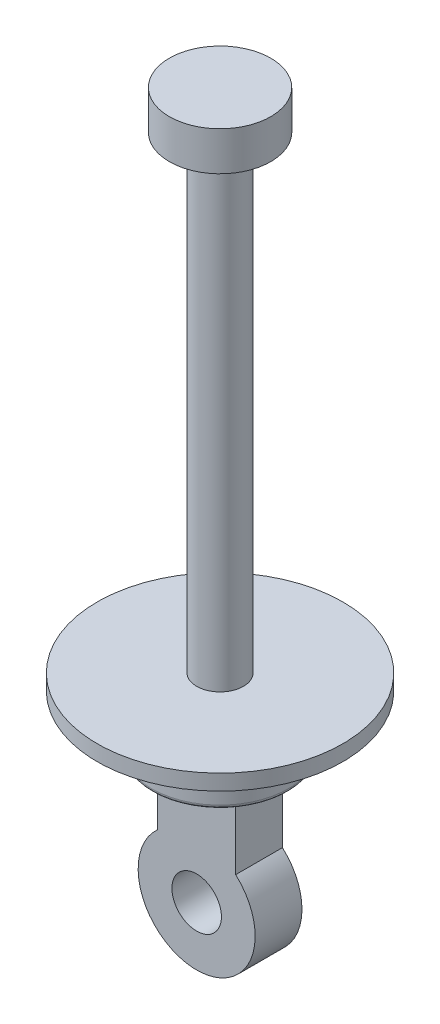
SolidWorks part; units mm, degrees
ref_plane "Front Plane" through (0, 0, 0) normal (0, 0, 1) x (1, 0, 0)
ref_plane "Top Plane" through (0, 0, 0) normal (0, 1, 0) x (1, 0, 0)
ref_plane "Right Plane" through (0, 0, 0) normal (1, 0, 0) x (0, 0, -1)
sketch "Sketch1" plane through (0, 0, 0) normal (0, 0, 1) x (1, 0, 0)
  line L1 (-15, 15) -> (15, 15)
  line L2 (-15, 15) -> (-15, -15)
  line L4 (15, 15) -> (15, -15)
  arc A0 (-15, -15) -> (15, -15) centre (0, -15) ccw
  dimension "D1" = 30
  dimension "D2" = 15
  dimension "D3" = 30
  dimension "D4" = 30
  dimension "D5" = 15
extrude "Boss-Extrude1" add sketch "Sketch1" along normal mid plane 12
sketch "Sketch2" plane through (0, 0, 6) normal (0, 0, 1) x (1, 0, 0)
  circle A0 centre (0, -15) radius 6.35
  dimension "D1" = 12.7
extrude "Cut-Extrude1" cut sketch "Sketch2" against normal through all
sketch "Sketch3" plane through (0, 0, 6) normal (0, 0, 1) x (1, 0, 0)
  line L0 (-10, -3.8197) -> (-10, 15)
  line L1 (15, 15) -> (-15, 15) construction
  line L2 (-15, 15) -> (-10, 15)
  line L4 (-15, 15) -> (-15, -15) construction
  line L5 (-15, -15) -> (15, -15) construction
  line L6 (-15, 15) -> (-15, -15)
  line L7 (0, 18.2249) -> (0, -18.3661) construction
  line L8 (15, 15) -> (15, -15)
  line L9 (15, 15) -> (10, 15)
  line L10 (10, -3.8197) -> (10, 15)
  arc A0 (-10, -3.8197) -> (-15, -15) centre (0, -15) ccw
  arc A3 (10, -3.8197) -> (15, -15) centre (0, -15) cw
  point P12 (-10, 15)
  point P25 (10, 15)
  dimension "D2" = 5
extrude "Cut-Extrude2" cut sketch "Sketch3" against normal through all
sketch "Sketch4" plane through (0, 15, 0) normal (0, 1, 0) x (1, 0, 0)
  circle A0 centre (0, 0) radius 17.5
  dimension "D1" = 35
extrude "Boss-Extrude2" add sketch "Sketch4" along normal blind 10
fillet "Fillet3" radius 1 1 edges at (0, 15, 17.5)
fillet "Fillet4" radius 2 4 edges at (-10, 15, 0) (0, 15, 6) (10, 15, 0) (0, 15, -6)
sketch "Sketch5" plane through (0, 0, 0) normal (1, 0, 0) x (0, 0, -1)
  line L0 (0, 0) -> (0, 46.9729) construction
  line L1 (0, 25) -> (-22.5, 25)
  line L2 (17.5, 25) -> (-17.5, 25) construction
  line L3 (-22.5, 25) -> (-31.5, 29)
  line L4 (-31.5, 29) -> (-31.5, 33)
  line L5 (-31.5, 33) -> (0, 33)
  line L6 (-17.5, 25) -> (-17.5, 16) construction
  line L7 (0, 25) -> (0, 33)
  dimension "D1" = 31.5
  dimension "D2" = 8
  dimension "D3" = 4
  dimension "D4" = 5
revolve "Revolve1" add sketch "Sketch5" angle 360 about L0
sketch "Sketch6" plane through (0, 33, 0) normal (0, 1, 0) x (1, 0, 0)
  circle A0 centre (0, 0) radius 6
  dimension "D1" = 12
extrude "Boss-Extrude3" add sketch "Sketch6" along normal blind 130
sketch "Sketch7" plane through (0, 163, 0) normal (0, 1, 0) x (1, 0, 0)
  circle A0 centre (0, 0) radius 13
  dimension "D1" = 26
extrude "Boss-Extrude4" add sketch "Sketch7" against normal blind 10
